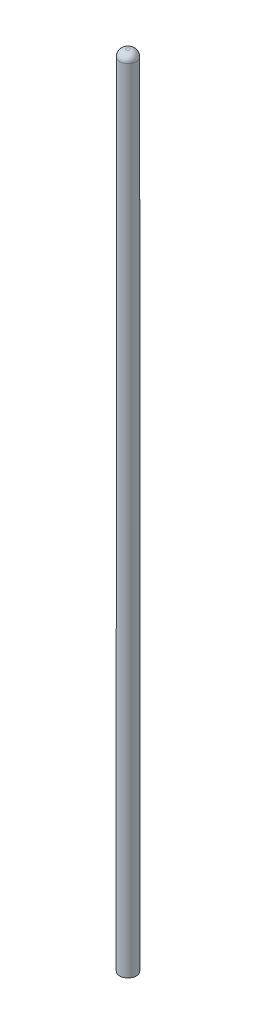
SolidWorks part; units mm, degrees
ref_plane "Front Plane" through (0, 0, 0) normal (0, 0, 1) x (1, 0, 0)
ref_plane "Top Plane" through (0, 0, 0) normal (0, 1, 0) x (1, 0, 0)
ref_plane "Right Plane" through (0, 0, 0) normal (1, 0, 0) x (0, 0, -1)
sketch "Sketch1" plane through (0, 0, 0) normal (0, 1, 0) x (1, 0, 0)
  circle A0 centre (0, 0) radius 1.5875
  dimension "D1" = 3.175
extrude "Boss-Extrude1" add sketch "Sketch1" along normal blind 152.4
fillet "Fillet2" radius 1.27 1 edges at (0, 152.4, 1.5875)
